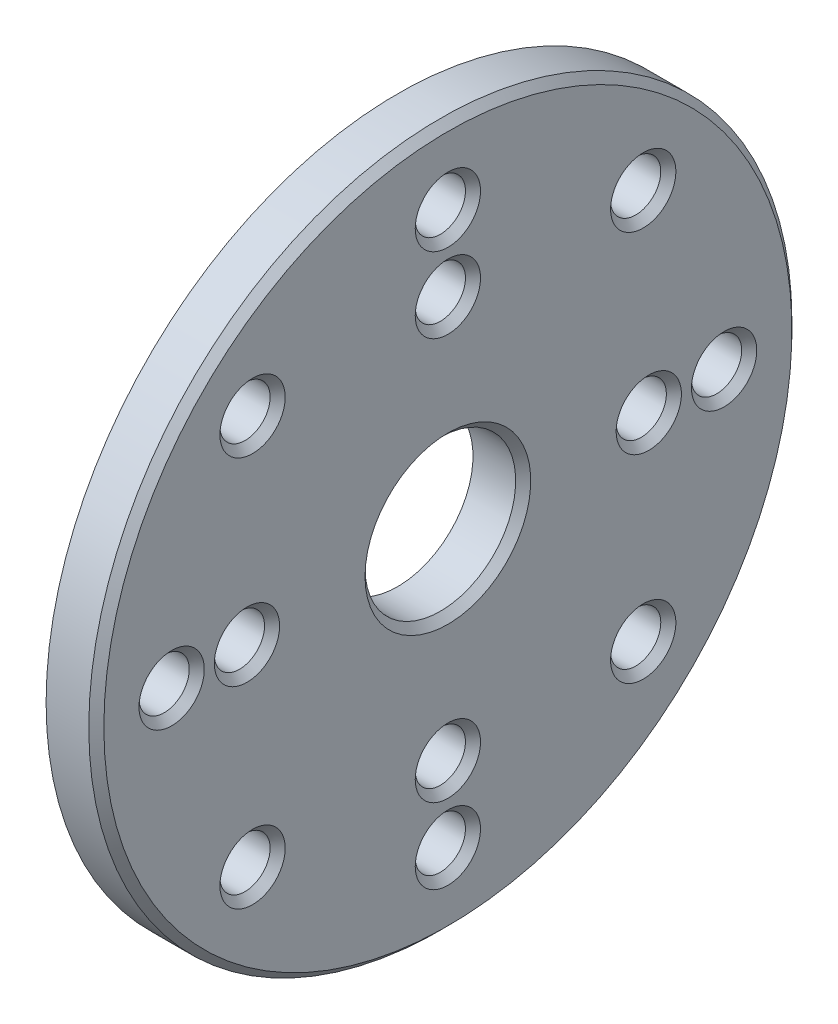
SolidWorks part; units mm, degrees
ref_plane "Ön Düzlem" through (0, 0, 0) normal (0, 0, 1) x (1, 0, 0)
ref_plane "Üst Düzlem" through (0, 0, 0) normal (0, 1, 0) x (1, 0, 0)
ref_plane "Sağ Düzlem" through (0, 0, 0) normal (1, 0, 0) x (0, 0, -1)
sketch "Sketch1" plane through (0, 0, 0) normal (0, 0, 1) x (1, 0, 0)
  line L0 (0, 3) -> (-2, 3)
  line L1 (-2, 3) -> (-2, 14)
  line L2 (-2, 14) -> (0, 14)
  line L3 (0, 14) -> (0, 3)
  line L8 (0, 0) -> (3.3862, 0) construction
  dimension "D1" = 14
  dimension "D2" = 2
  dimension "D7" = 3
revolve "Revolve1" add sketch "Sketch1" angle 360 about L8
sketch "Sketch2" plane through (0, 0, 0) normal (1, 0, 0) x (0, 0, -1)
  circle A0 centre (0, 0) radius 11 construction
  circle A3 centre (0, 11) radius 1
  dimension "D2" = 22
  dimension "D3" = 2
extrude "Cut-Extrude1" cut sketch "Sketch2" against normal through all
pattern_circular "CirPattern2" count 8 over 360 about axis through (0, 0, 0) along (1, 0, 0) of "Cut-Extrude1"
sketch "Sketch3" plane through (0, 0, 0) normal (1, 0, 0) x (0, 0, -1)
  circle A0 centre (0, 0) radius 8 construction
  circle A1 centre (0, 8) radius 1
  dimension "D1" = 2
  dimension "D2" = 16
extrude "Cut-Extrude2" cut sketch "Sketch3" against normal through all
pattern_circular "CirPattern3" count 4 over 360 about axis through (0, 0, 0) along (1, 0, 0) of "Cut-Extrude2"
chamfer "Chamfer1" distance 0.3 angle 45 14 edges at (0, 0, 3) (0, 0, 14) (0, 11, -1) (0, 7.0711, -8.4853) (0, -1, -11) (0, -8.4853, -7.0711) (0, -11, 1) (0, -7.0711, 8.4853) (0, 1, 11) (0, 8.4853, 7.0711) (0, 8, -1) (0, -1, -8) (0, -8, 1) (0, 1, 8)
